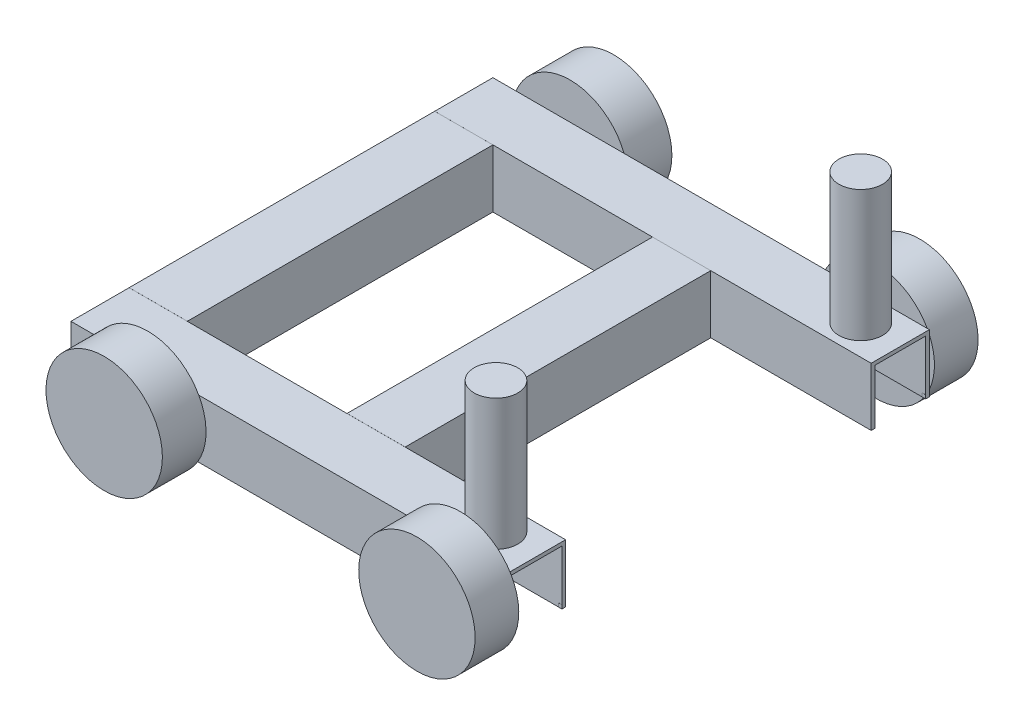
SolidWorks part; units mm, degrees
ref_plane "Front Plane" through (0, 0, 0) normal (0, 0, 1) x (1, 0, 0)
ref_plane "Top Plane" through (0, 0, 0) normal (0, 1, 0) x (1, 0, 0)
ref_plane "Right Plane" through (0, 0, 0) normal (1, 0, 0) x (0, 0, -1)
sketch "Sketch1" plane through (0, 0, 0) normal (0, 1, 0) x (1, 0, 0)
  line L0 (-167.5815, 100.2679) -> (213.4185, 100.2679)
  line L1 (-167.5543, -217.2885) -> (213.4457, -217.2885)
  line L2 (-167.5543, -217.2885) -> (-167.5543, -268.0885)
  line L3 (-167.5543, -268.0885) -> (213.4457, -268.0885)
  line L4 (213.4457, -217.2885) -> (213.4457, -268.0885)
  line L5 (22.5705, 49.4675) -> (73.3705, 49.4675)
  line L6 (22.5705, 49.4675) -> (22.5705, -217.2325)
  line L7 (22.5705, -217.2325) -> (73.3705, -217.2325)
  line L8 (73.3705, 49.4675) -> (73.3705, -217.2325)
  line L9 (-167.5815, 100.2679) -> (-167.5815, 49.4679)
  line L10 (-167.5815, 49.4679) -> (213.4185, 49.4679)
  line L11 (213.4185, 100.2679) -> (213.4185, 49.4679)
  line L12 (-167.5804, 49.456) -> (-116.7804, 49.456)
  line L13 (-167.5804, 49.456) -> (-167.5804, -217.244)
  line L14 (-167.5804, -217.244) -> (-116.7804, -217.244)
  line L15 (-116.7804, 49.456) -> (-116.7804, -217.244)
  line L16 (73.3705, 43.3308) -> (213.0705, 43.3308)
  dimension "D1" = 381
  dimension "D2" = 50.8
  dimension "D3" = 266.7
  dimension "D4" = 50.8
  dimension "D5" = 139.7
extrude "Boss-Extrude1" add sketch "Sketch1" along normal blind 50.8 contours L15 L12 L13 L14 | L4 L1 L2 L3 | L11 L0 L9 L10 | L6 L5 L8 L7
shell "Shell1" thickness 3.175
shell "Shell2" thickness 3.175
shell "Shell3" thickness 3.175
shell "Shell4" thickness 3.175
sketch "Sketch2" plane through (213.4457, 0, 0) normal (1, 0, 0) x (0, 0, -1)
  line L8 (-264.9135, 3.175) -> (-264.9135, 0)
  line L9 (-264.9135, 0) -> (-220.4977, 0)
  line L10 (-217.2885, 0) -> (-268.0885, 0) construction
  line L11 (-220.4977, 0) -> (-220.4977, 3.175)
  line L12 (-264.9135, 3.175) -> (-220.4635, 3.175)
  line L13 (-220.4635, 3.175) -> (-220.4635, 47.625)
  line L14 (-220.4635, 47.625) -> (-264.9135, 47.625)
  line L15 (-264.9135, 47.625) -> (-264.9135, 3.175)
  line L16 (-220.4977, 3.175) -> (-220.4635, 3.175)
  line L17 (-220.4635, 3.175) -> (-220.4635, 47.625)
  line L18 (-220.4635, 47.625) -> (-264.9135, 47.625)
  line L19 (-264.9135, 47.625) -> (-264.9135, 3.175)
  dimension "D1" = 3.175
extrude "Cut-Extrude2" cut sketch "Sketch2" against normal blind 448.056
sketch "Sketch3" plane through (213.4185, 0, 0) normal (1, 0, 0) x (0, 0, -1)
  line L0 (52.6429, 3.175) -> (52.6429, 0)
  line L1 (52.6429, 0) -> (97.0654, 0)
  line L2 (100.2679, 0) -> (49.4679, 0) construction
  line L3 (97.0654, 0) -> (97.0379, 3.175)
  line L8 (52.6429, 3.175) -> (97.0929, 3.175)
  line L9 (97.0929, 3.175) -> (97.0929, 47.625)
  line L10 (97.0929, 47.625) -> (52.6429, 47.625)
  line L11 (52.6429, 47.625) -> (52.6429, 3.175)
  line L12 (97.0379, 3.175) -> (97.0929, 3.175)
  line L13 (97.0929, 3.175) -> (97.0929, 47.625)
  line L14 (97.0929, 47.625) -> (52.6429, 47.625)
  line L15 (52.6429, 47.625) -> (52.6429, 3.175)
  dimension "D1" = 3.175
extrude "Cut-Extrude3" cut sketch "Sketch3" against normal blind 448.056
sketch "Sketch4" plane through (0, 50.8, 0) normal (0, 1, 0) x (1, 0, 0)
  circle A0 centre (176.8975, -241.5143) radius 19.05
  circle A1 centre (178.3364, 75.4247) radius 19.05
  point P2 (0, 0)
  point P3 (176.8975, -241.5143)
  point P6 (184.2967, -188.2399)
  point P7 (176.8975, 80.4609)
  point P8 (0, 0)
  point P9 (0, 0)
  point P10 (0, 0)
  dimension "D1" = 38.1
extrude "Boss-Extrude2" add sketch "Sketch4" along normal blind 114.3 contours A1 | A0
sketch "Sketch5" plane through (0, 0, 268.0885) normal (0, 0, 1) x (1, 0, 0)
  circle A0 centre (172.5657, 26.157) radius 50.8
  circle A1 centre (-100.4275, 26.157) radius 50.8
  point P2 (170.6433, 29.3612)
  point P3 (0, 0)
  point P4 (179.6149, 18.4671)
  point P5 (0, 0)
  point P6 (0, 0)
  point P9 (-100.4275, 26.157)
  dimension "D1" = 101.6
extrude "Boss-Extrude3" add sketch "Sketch5" along normal blind 38.1
sketch "Sketch6" plane through (0, 0, -100.2679) normal (0, 0, -1) x (-1, 0, 0)
  circle A0 centre (-167.0432, 26.2625) radius 50.8
  circle A2 centre (100.2292, 31.9756) radius 50.8
  point P4 (102.2831, 26.2625)
  point P5 (0, 0)
  point P6 (0, 0)
  point P7 (0, 0)
  point P8 (100.2292, 31.9756)
  dimension "D1" = 101.6
extrude "Boss-Extrude5" add sketch "Sketch6" along normal blind 38.1
